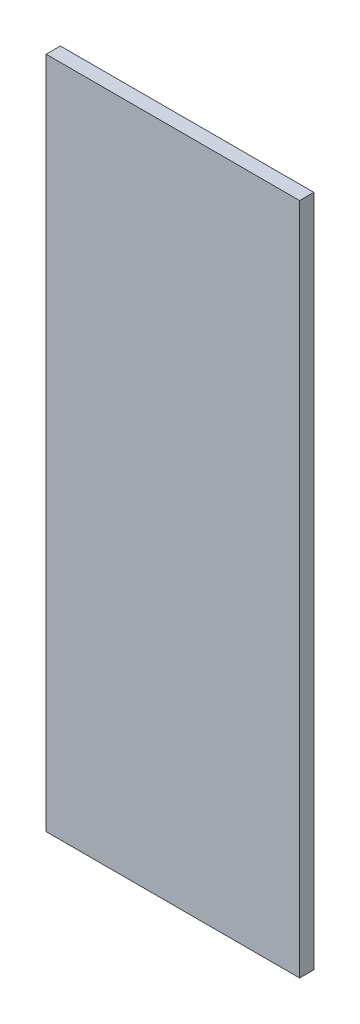
SolidWorks part; units mm, degrees
material "ABS"
ref_plane "X-Y Datum" through (0, 0, 0) normal (0, 0, 1) x (1, 0, 0)
ref_plane "X-Z Datum" through (0, 0, 0) normal (0, 1, 0) x (1, 0, 0)
ref_plane "Y-Z Datum" through (0, 0, 0) normal (1, 0, 0) x (0, 0, -1)
sketch "Sketch2" plane through (0, 0, 0) normal (0, 0, 1) x (1, 0, 0)
  line L1 (-28.275, -75.1) -> (28.275, -75.1)
  line L2 (-28.275, -75.1) -> (-28.275, 75.1)
  line L3 (-28.275, 75.1) -> (28.275, 75.1)
  line L4 (28.275, -75.1) -> (28.275, 75.1)
  line L5 (-28.275, -75.1) -> (28.275, 75.1) construction
  line L6 (-28.275, 75.1) -> (28.275, -75.1) construction
  point P0 (0, 0)
  dimension "D1" = 150.2
  dimension "D2" = 56.55
extrude "Boss-Extrude1" add sketch "Sketch2" along normal blind 3.175
